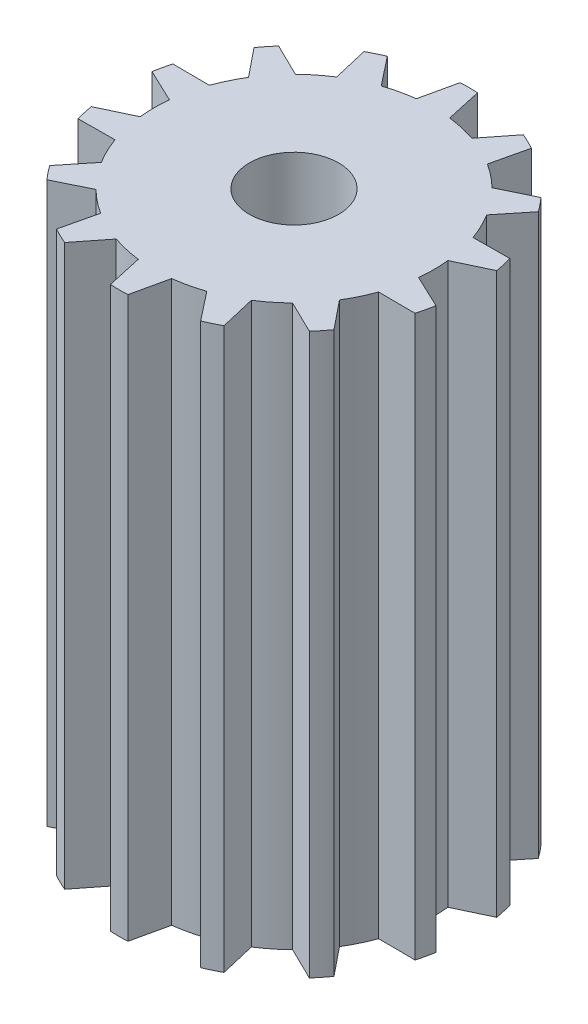
SolidWorks part; units mm, degrees
ref_plane "Front Plane" through (0, 0, 0) normal (0, 0, 1) x (1, 0, 0)
ref_plane "Top Plane" through (0, 0, 0) normal (0, 1, 0) x (1, 0, 0)
ref_plane "Right Plane" through (0, 0, 0) normal (1, 0, 0) x (0, 0, -1)
sketch "Sketch1" plane through (0, 0, 0) normal (0, 1, 0) x (1, 0, 0)
  line L0 (0, 0) -> (0, 50000) construction
  line L1 (0, 0) -> (50000, 0) construction
  line L2 (-0.25, 4.9937) -> (-0.4766, 3.9715)
  line L3 (0.25, 4.9937) -> (0.4766, 3.9715)
  line L4 (2.3919, 4.3907) -> (2.1526, 3.3714)
  line L5 (1.9415, 4.6077) -> (1.2937, 3.785)
  line L6 (4.0601, 2.9181) -> (3.4022, 2.1035)
  line L7 (3.7484, 3.309) -> (2.8079, 2.8488)
  line L8 (4.9242, 0.8675) -> (3.978, 0.4191)
  line L9 (4.8129, 1.3549) -> (3.7659, 1.3484)
  line L10 (4.8129, -1.3549) -> (3.7659, -1.3484)
  line L11 (4.9242, -0.8675) -> (3.978, -0.4191)
  line L12 (3.7484, -3.309) -> (2.8079, -2.8488)
  line L13 (4.0601, -2.9181) -> (3.4022, -2.1035)
  line L14 (1.9415, -4.6077) -> (1.2937, -3.785)
  line L15 (2.3919, -4.3907) -> (2.1526, -3.3714)
  line L16 (-0.25, -4.9937) -> (-0.4766, -3.9715)
  line L17 (0.25, -4.9937) -> (0.4766, -3.9715)
  line L18 (-2.3919, -4.3907) -> (-2.1526, -3.3714)
  line L19 (-1.9415, -4.6077) -> (-1.2937, -3.785)
  line L20 (-4.0601, -2.9181) -> (-3.4022, -2.1035)
  line L21 (-3.7484, -3.309) -> (-2.8079, -2.8488)
  line L22 (-4.9242, -0.8675) -> (-3.978, -0.4191)
  line L23 (-4.8129, -1.3549) -> (-3.7659, -1.3484)
  line L24 (-4.8129, 1.3549) -> (-3.7659, 1.3484)
  line L25 (-4.9242, 0.8675) -> (-3.978, 0.4191)
  line L26 (-3.7484, 3.309) -> (-2.8079, 2.8488)
  line L27 (-4.0601, 2.9181) -> (-3.4022, 2.1035)
  line L28 (-1.9415, 4.6077) -> (-1.2937, 3.785)
  line L29 (-2.3919, 4.3907) -> (-2.1526, 3.3714)
  circle A0 centre (0, 0) radius 4.5 construction
  arc A2 (-0.4766, 3.9715) -> (-1.2937, 3.785) centre (0, 0) ccw
  arc A3 (0.25, 4.9937) -> (-0.25, 4.9937) centre (0, 0) ccw
  arc A4 (2.3919, 4.3907) -> (1.9415, 4.6077) centre (0, 0) ccw
  arc A5 (4.0601, 2.9181) -> (3.7484, 3.309) centre (0, 0) ccw
  arc A6 (4.9242, 0.8675) -> (4.8129, 1.3549) centre (0, 0) ccw
  arc A7 (4.8129, -1.3549) -> (4.9242, -0.8675) centre (0, 0) ccw
  arc A8 (3.7484, -3.309) -> (4.0601, -2.9181) centre (0, 0) ccw
  arc A9 (1.9415, -4.6077) -> (2.3919, -4.3907) centre (0, 0) ccw
  arc A10 (-0.25, -4.9937) -> (0.25, -4.9937) centre (0, 0) ccw
  arc A11 (-2.3919, -4.3907) -> (-1.9415, -4.6077) centre (0, 0) ccw
  arc A12 (-4.0601, -2.9181) -> (-3.7484, -3.309) centre (0, 0) ccw
  arc A13 (-4.9242, -0.8675) -> (-4.8129, -1.3549) centre (0, 0) ccw
  arc A14 (-4.8129, 1.3549) -> (-4.9242, 0.8675) centre (0, 0) ccw
  arc A15 (-3.7484, 3.309) -> (-4.0601, 2.9181) centre (0, 0) ccw
  arc A16 (-1.9415, 4.6077) -> (-2.3919, 4.3907) centre (0, 0) ccw
  arc A17 (1.2937, 3.785) -> (0.4766, 3.9715) centre (0, 0) ccw
  arc A18 (2.8079, 2.8488) -> (2.1526, 3.3714) centre (0, 0) ccw
  arc A19 (-2.1526, 3.3714) -> (-2.8079, 2.8488) centre (0, 0) ccw
  arc A20 (-3.4022, 2.1035) -> (-3.7659, 1.3484) centre (0, 0) ccw
  arc A21 (-3.978, 0.4191) -> (-3.978, -0.4191) centre (0, 0) ccw
  arc A22 (-3.7659, -1.3484) -> (-3.4022, -2.1035) centre (0, 0) ccw
  arc A23 (-2.8079, -2.8488) -> (-2.1526, -3.3714) centre (0, 0) ccw
  arc A24 (-1.2937, -3.785) -> (-0.4766, -3.9715) centre (0, 0) ccw
  arc A25 (0.4766, -3.9715) -> (1.2937, -3.785) centre (0, 0) ccw
  arc A26 (2.1526, -3.3714) -> (2.8079, -2.8488) centre (0, 0) ccw
  arc A27 (3.4022, -2.1035) -> (3.7659, -1.3484) centre (0, 0) ccw
  arc A28 (3.978, -0.4191) -> (3.978, 0.4191) centre (0, 0) ccw
  arc A29 (3.7659, 1.3484) -> (3.4022, 2.1035) centre (0, 0) ccw
  point P79 (0, 0)
  dimension "D1" = 9
  dimension "D2" = 10
  dimension "D3" = 8
  dimension "D6" = 14
  dimension "D4" = 25
  dimension "D5" = 0.5
extrude "Boss-Extrude1" add sketch "Sketch1" along normal blind 16
sketch "Sketch2" plane through (0, 0, 0) normal (0, -1, 0) x (1, 0, 0)
  circle A0 centre (0, 0) radius 1.275
  dimension "D1" = 2.55
extrude "Cut-Extrude1" cut sketch "Sketch2" against normal through all
